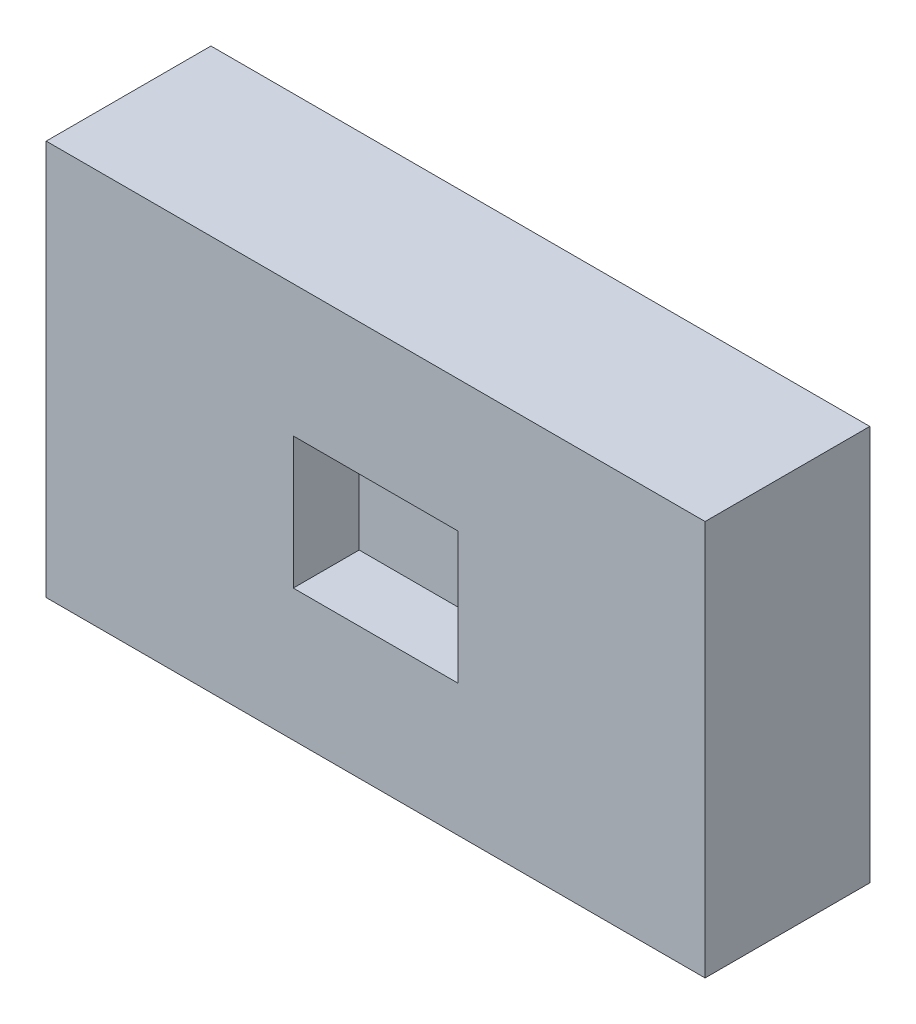
SolidWorks part; units mm, degrees
ref_plane "Front Plane" through (0, 0, 0) normal (0, 0, 1) x (1, 0, 0)
ref_plane "Top Plane" through (0, 0, 0) normal (0, 1, 0) x (1, 0, 0)
ref_plane "Right Plane" through (0, 0, 0) normal (1, 0, 0) x (0, 0, -1)
sketch "RectangleSketch" plane through (0, 0, 0) normal (0, 0, 1) x (1, 0, 0)
  line L1 (0, 0) -> (40, 0)
  line L2 (0, 0) -> (0, 24)
  line L3 (0, 24) -> (40, 24)
  line L4 (40, 0) -> (40, 24)
  dimension "width_mm" = 40
  dimension "height_mm" = 24
extrude "BlindBoss" add sketch "RectangleSketch" along normal blind 10 separate body
sketch "CutSketch" plane through (0, 0, 10) normal (0, 0, 1) x (1, 0, 0)
  line L1 (15, 8) -> (25, 8)
  line L2 (15, 8) -> (15, 16)
  line L3 (15, 16) -> (25, 16)
  line L4 (25, 8) -> (25, 16)
  dimension "cut_width_mm" = 10
  dimension "cut_height_mm" = 8
  dimension "cut_left_mm" = 15
  dimension "cut_bottom_mm" = 8
extrude "BlindCut" cut sketch "CutSketch" against normal blind 4
equation "\"cut_left_mm@CutSketch\" = (\"width_mm@RectangleSketch\" - \"cut_width_mm@CutSketch\") / 2"
equation "\"cut_bottom_mm@CutSketch\" = (\"height_mm@RectangleSketch\" - \"cut_height_mm@CutSketch\") / 2"
